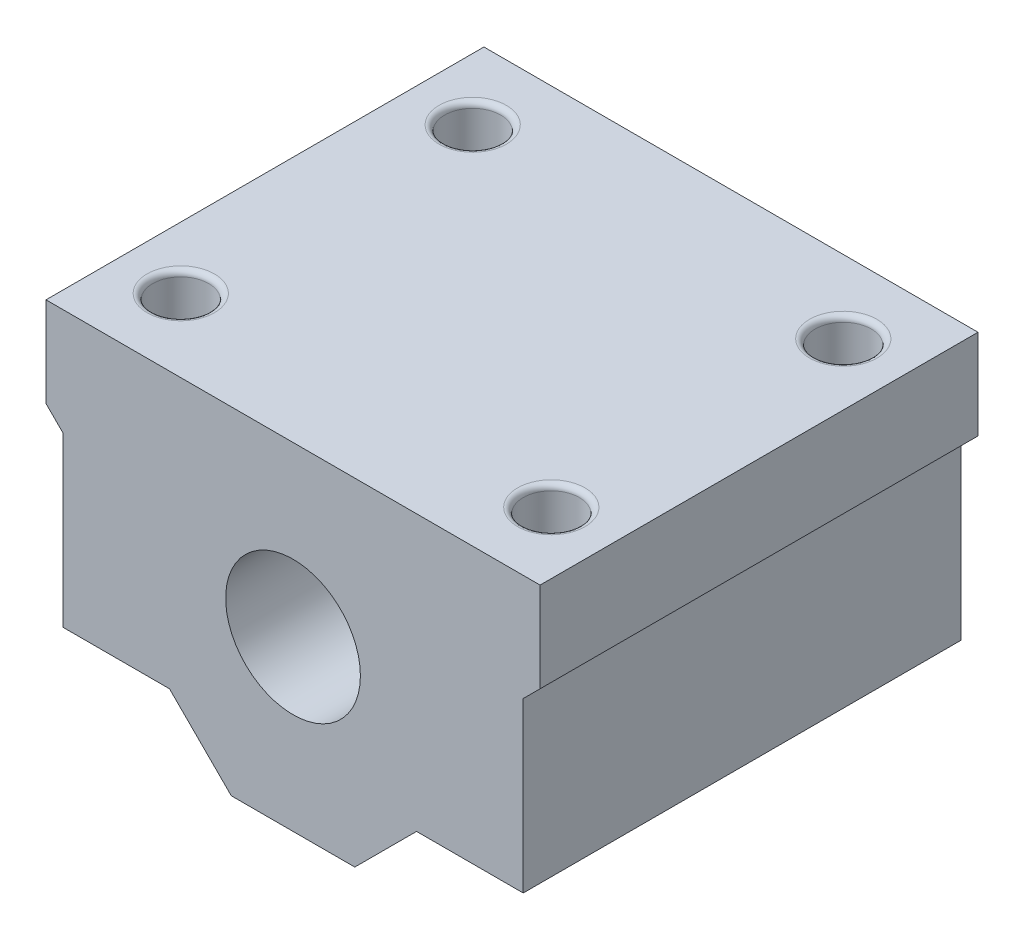
SolidWorks part; units mm, degrees
ref_plane "Ön Düzlem" through (0, 0, 0) normal (0, 0, 1) x (1, 0, 0)
ref_plane "Üst Düzlem" through (0, 0, 0) normal (0, 1, 0) x (1, 0, 0)
ref_plane "Sağ Düzlem" through (0, 0, 0) normal (1, 0, 0) x (0, 0, -1)
sketch "Çizim2" plane through (0, 0, 0) normal (0, 0, 1) x (1, 0, 0)
  line L0 (0, 19.2039) -> (0, -22.0439) construction
  line L1 (22, 15) -> (-22, 15)
  line L2 (-22, 15) -> (-22, 7)
  line L3 (-22, 7) -> (-20.5, 5.5)
  line L4 (-20.5, 5.5) -> (-20.5, -9.5)
  line L5 (-20.5, -9.5) -> (-11, -9.5)
  line L6 (-11, -9.5) -> (-5.5, -15)
  line L7 (-5.5, -15) -> (5.5, -15)
  line L8 (11, -9.5) -> (5.5, -15)
  line L9 (20.5, -9.5) -> (11, -9.5)
  line L10 (20.5, 5.5) -> (20.5, -9.5)
  line L11 (22, 7) -> (20.5, 5.5)
  line L12 (22, 15) -> (22, 7)
  circle A0 centre (0, 0) radius 6
  point P23 (0, -15)
  point P28 (0, 15)
  dimension "D1" = 12
  dimension "D2" = 15
  dimension "D3" = 22
  dimension "D4" = 30
  dimension "D5" = 24.5
  dimension "D6" = 8
  dimension "D7" = 1.5
  dimension "D8" = 9.5
  dimension "D9" = 135
  dimension "D10" = 135
extrude "Yükseklik-Ekstrüzyon1" add sketch "Çizim2" along normal blind 39
sketch "Çizim3" plane through (0, -9.5, 0) normal (0, -1, 0) x (1, 0, 0)
  line L0 (0, 19.5) -> (0, -2.7991) construction
  line L1 (22, 19.5) -> (0, 19.5) construction
  line L2 (22, 39) -> (22, 0) construction
  line L6 (16.5, 6.5) -> (-16.5, 6.5) construction
  line L10 (16.5, 6.5) -> (16.5, 32.5) construction
  line L11 (16.5, 32.5) -> (-16.5, 32.5) construction
  line L12 (-16.5, 6.5) -> (-16.5, 32.5) construction
  line L13 (16.5, 6.5) -> (-16.5, 32.5) construction
  line L14 (16.5, 32.5) -> (-16.5, 6.5) construction
  circle A3 centre (16.5, 32.5) radius 2.5
  circle A4 centre (-16.5, 32.5) radius 2.5
  circle A5 centre (-16.5, 6.5) radius 2.5
  circle A6 centre (16.5, 6.5) radius 2.5
  point P16 (10.0654, 32.5)
  point P17 (0, 0)
  point P18 (16.5, 32.5)
  dimension "D3" = 5
  dimension "D2" = 26
  dimension "D4" = 33
extrude "Kes-Ekstrüzyon1" cut sketch "Çizim3" against normal blind 39
chamfer "Pah2" distance 1.5 angle 45 1 edges at (6, 0, 0)
fillet "Fillet2" radius 0.5 4 edges at (-16.5, 15, 30) (16.5, 15, 30) (16.5, 15, 4) (-16.5, 15, 4)
